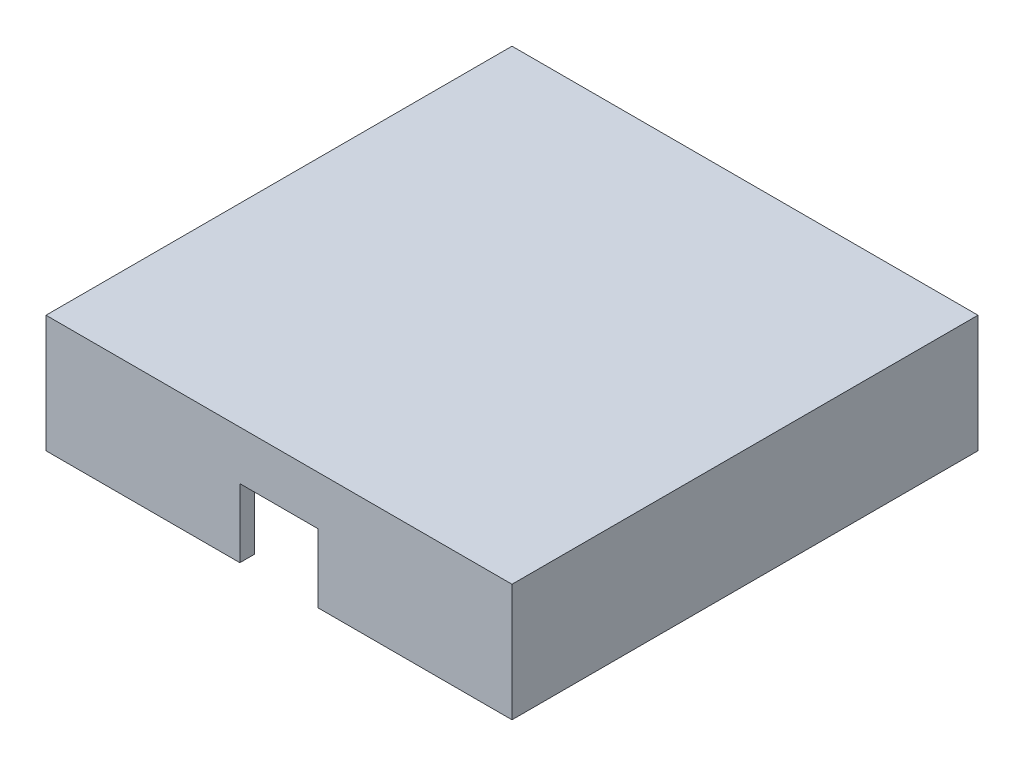
SolidWorks part; units mm, degrees
ref_plane "Front Plane" through (0, 0, 0) normal (0, 0, 1) x (1, 0, 0)
ref_plane "Top Plane" through (0, 0, 0) normal (0, 1, 0) x (1, 0, 0)
ref_plane "Right Plane" through (0, 0, 0) normal (1, 0, 0) x (0, 0, -1)
sketch "Sketch1" plane through (0, 0, 0) normal (0, 1, 0) x (1, 0, 0)
  line L1 (0, 0) -> (47.625, 0)
  line L2 (0, 0) -> (0, 47.625)
  line L3 (0, 47.625) -> (47.625, 47.625)
  line L4 (47.625, 0) -> (47.625, 47.625)
  dimension "D1" = 47.625
  dimension "D2" = 47.625
extrude "Boss-Extrude1" add sketch "Sketch1" along normal blind 2
sketch "Sketch2" plane through (0, 0, 0) normal (0, -1, 0) x (1, 0, 0)
  line L1 (15.6808, -28.4087) -> (28.4087, -15.6808)
  line L2 (15.6808, -28.4087) -> (19.2163, -31.9442)
  line L3 (19.2163, -31.9442) -> (31.9442, -19.2163)
  line L4 (28.4087, -15.6808) -> (31.9442, -19.2163)
  line L6 (22.0447, -22.0447) -> (25.5803, -25.5803) construction
  line L7 (17.4485, -30.1765) -> (30.1765, -17.4485) construction
  line L8 (0, 0) -> (47.625, -47.625) construction
  line L14 (47.625, 0) -> (0, -47.625) construction
  dimension "D1" = 18
  dimension "D2" = 5
extrude "Boss-Extrude2" add sketch "Sketch2" along normal blind 4
sketch "Sketch4" plane through (6.364, 0, 6.364) normal (0.7071, 0, 0.7071) x (0.7071, 0, -0.7071)
  line L0 (33.676, -4) -> (33.676, 0) construction
  line L1 (36.176, -4) -> (31.176, -4) construction
  line L2 (36.176, 0) -> (31.176, 0) construction
  circle A0 centre (33.676, -1.5) radius 1.5
  dimension "D1" = 3
extrude "Cut-Extrude2" cut sketch "Sketch4" against normal through all
sketch "Sketch5" plane through (0, 0, 0) normal (0, -1, 0) x (1, 0, 0)
  line L0 (46.125, -1.5) -> (1.5, -1.5)
  line L1 (1.5, -1.5) -> (1.5, -46.125)
  line L2 (1.5, -46.125) -> (46.125, -46.125)
  line L3 (46.125, -46.125) -> (46.125, -1.5)
  line L4 (0, 0) -> (0, -47.625)
  line L5 (0, -47.625) -> (47.625, -47.625)
  line L6 (47.625, -47.625) -> (47.625, 0)
  line L7 (47.625, 0) -> (0, 0)
  line L8 (0, 0) -> (0, -47.625)
  line L9 (0, -47.625) -> (47.625, -47.625)
  line L10 (47.625, -47.625) -> (47.625, 0)
  line L11 (47.625, 0) -> (0, 0)
  dimension "D1" = 0
  dimension "D2" = 1.5
extrude "Boss-Extrude3" add sketch "Sketch5" along normal blind 10
sketch "Sketch6" plane through (0, 0, 0) normal (0, 0, 1) x (1, 0, 0)
  line L0 (47.625, -10) -> (0, -10) construction
  line L1 (19.8125, -10) -> (27.8125, -10)
  line L2 (19.8125, -10) -> (19.8125, -3)
  line L3 (19.8125, -3) -> (27.8125, -3)
  line L4 (27.8125, -10) -> (27.8125, -3)
  line L5 (23.8125, 2) -> (23.8125, -10) construction
  line L6 (0, 2) -> (47.625, 2) construction
  dimension "D1" = 8
  dimension "D2" = 7
extrude "Cut-Extrude3" cut sketch "Sketch6" against normal blind 2
